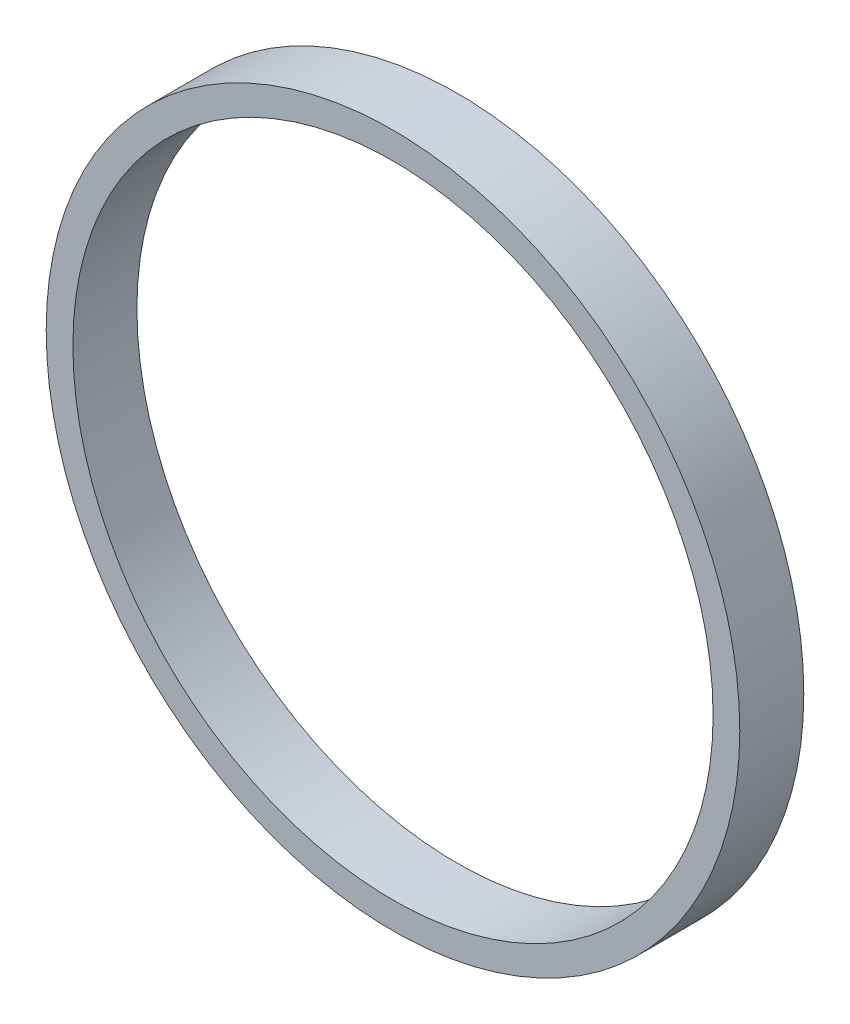
SolidWorks part; units mm, degrees
ref_plane "Front Plane" through (0, 0, 0) normal (0, 0, 1) x (1, 0, 0)
ref_plane "Top Plane" through (0, 0, 0) normal (0, 1, 0) x (1, 0, 0)
ref_plane "Right Plane" through (0, 0, 0) normal (1, 0, 0) x (0, 0, -1)
sketch "Sketch1" plane through (0, 0, 0) normal (0, 0, 1) x (1, 0, 0)
  circle A0 centre (0, 0) radius 32.5
  circle A1 centre (0, 0) radius 30
  dimension "D1" = 60
  dimension "D2" = 65
extrude "Boss-Extrude1" add sketch "Sketch1" along normal mid plane 6
